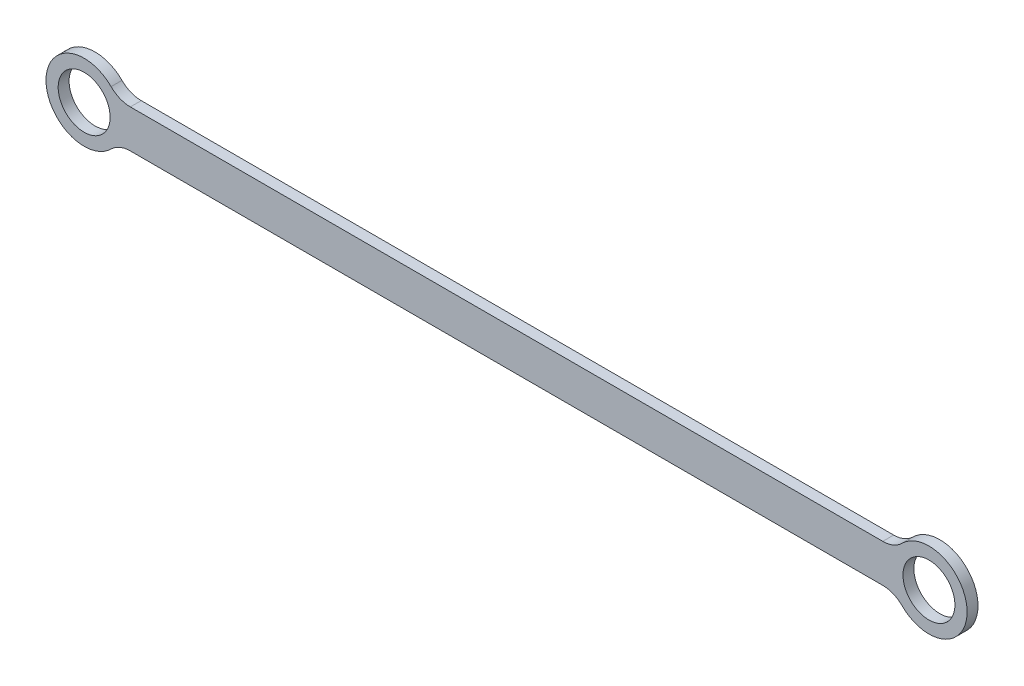
SolidWorks part; units mm, degrees
ref_plane "前视基准面" through (0, 0, 0) normal (0, 0, 1) x (1, 0, 0)
ref_plane "上视基准面" through (0, 0, 0) normal (0, 1, 0) x (1, 0, 0)
ref_plane "右视基准面" through (0, 0, 0) normal (1, 0, 0) x (0, 0, -1)
sketch "草图2" plane through (0, 0, 0) normal (0, 0, 1) x (1, 0, 0)
  line L0 (-138.0575, 6.9986) -> (138.0575, 6.9986)
  line L1 (138.0575, -6.9986) -> (-138.0575, -6.9986)
  circle A0 centre (-155, 0) radius 9.53
  circle A1 centre (155, 0) radius 9.53
  circle A2 centre (-155, 0) radius 14 construction
  circle A3 centre (155, 0) radius 14 construction
  arc A4 (145.1169, 9.9159) -> (145.1169, -9.9159) centre (155, 0) cw
  arc A5 (-145.1169, -9.9159) -> (-145.1169, 9.9159) centre (-155, 0) cw
  arc A6 (145.1169, 9.9159) -> (138.0575, 6.9986) centre (138.0575, 16.9986) cw
  arc A7 (145.1169, -9.9159) -> (138.0575, -6.9986) centre (138.0575, -16.9986) ccw
  arc A8 (-138.0575, -6.9986) -> (-145.1169, -9.9159) centre (-138.0575, -16.9986) ccw
  arc A9 (-138.0575, 6.9986) -> (-145.1169, 9.9159) centre (-138.0575, 16.9986) cw
  dimension "D1" = 10
extrude "凸台-拉伸2" add sketch "草图2" along normal blind 4
